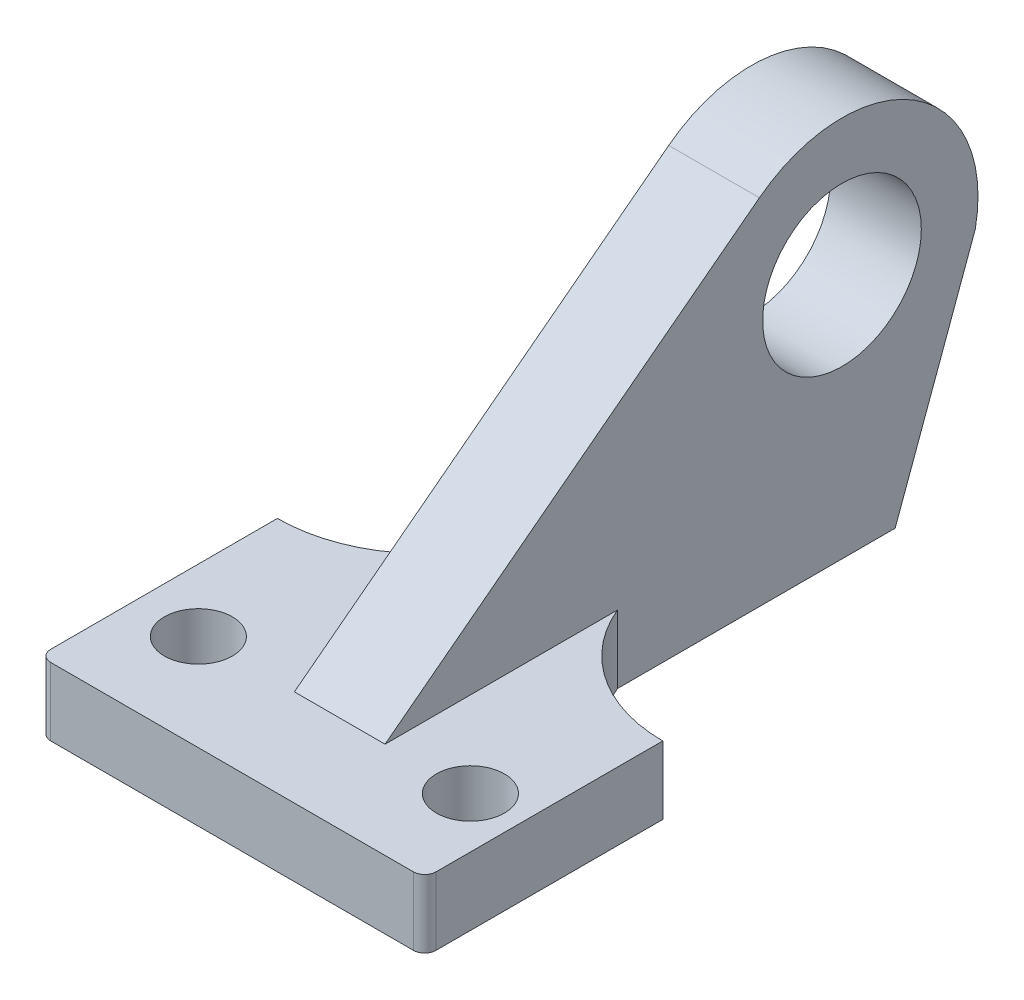
SolidWorks part; units mm, degrees
ref_plane "Front Plane" through (0, 0, 0) normal (0, 0, 1) x (1, 0, 0)
ref_plane "Top Plane" through (0, 0, 0) normal (0, 1, 0) x (1, 0, 0)
ref_plane "Right Plane" through (0, 0, 0) normal (1, 0, 0) x (0, 0, -1)
sketch "Sketch3" plane through (0, 0, 0) normal (0, 1, 0) x (1, 0, 0)
  line L0 (-27.5328, 0) -> (36.4672, 0)
  line L1 (38.4672, 2) -> (38.4672, 68)
  line L2 (38.4672, 68) -> (-29.5328, 68)
  line L3 (-29.5328, 68) -> (-29.5328, 2)
  line L4 (-3.5328, 68) -> (12.4672, 68)
  line L5 (-3.5328, 68) -> (12.4672, 68)
  arc A0 (38.4672, 42) -> (12.4672, 68) centre (38.4672, 68) cw
  arc A1 (-3.5328, 68) -> (-29.5328, 42) centre (-29.5328, 68) cw
  circle A2 centre (29.5257, 17) radius 6
  circle A3 centre (-18.4743, 17) radius 6
  arc A4 (-29.5328, 2) -> (-27.5328, 0) centre (-27.5328, 2) ccw
  arc A5 (38.4672, 2) -> (36.4672, 0) centre (36.4672, 2) cw
  point P17 (-29.5328, 0)
  point P20 (38.4672, 0)
  dimension "D4" = 26
  dimension "D6" = 26
  dimension "D7" = 26
  dimension "D9" = 17
  dimension "D12" = 2
  dimension "D1" = 68
  dimension "D2" = 68
  dimension "D3" = 42
  dimension "D5" = 42
  dimension "D8" = 26
  dimension "D10" = 17
  dimension "D11" = 48
extrude "Boss-Extrude3" add sketch "Sketch3" against normal blind 12 contours L2 A1 L3 L0 L1 A0
ref_plane "Plane2" through (6.4672, 0, 0) normal (1, 0, 0) x (0, 0, -1)
sketch "Sketch4" plane through (6.4672, 0, 0) normal (1, 0, 0) x (0, 0, -1)
  line L0 (17, 0) -> (83.0477, 50.4695)
  line L1 (2, 0) -> (42, 0) construction
  line L2 (17, 0) -> (17, -12)
  line L3 (2, -12) -> (42, -12) construction
  line L4 (17, -12) -> (107, -12)
  line L5 (107, -12) -> (121.1432, 26.6414)
  arc A0 (83.0477, 50.4695) -> (121.1432, 26.6414) centre (97.6196, 31.3997) cw
  circle A1 centre (97.6196, 31.3997) radius 14
  dimension "D2" = 24
  dimension "D3" = 17
  dimension "D1" = 90
extrude "Boss-Extrude4" add sketch "Sketch4" along normal mid plane 16
